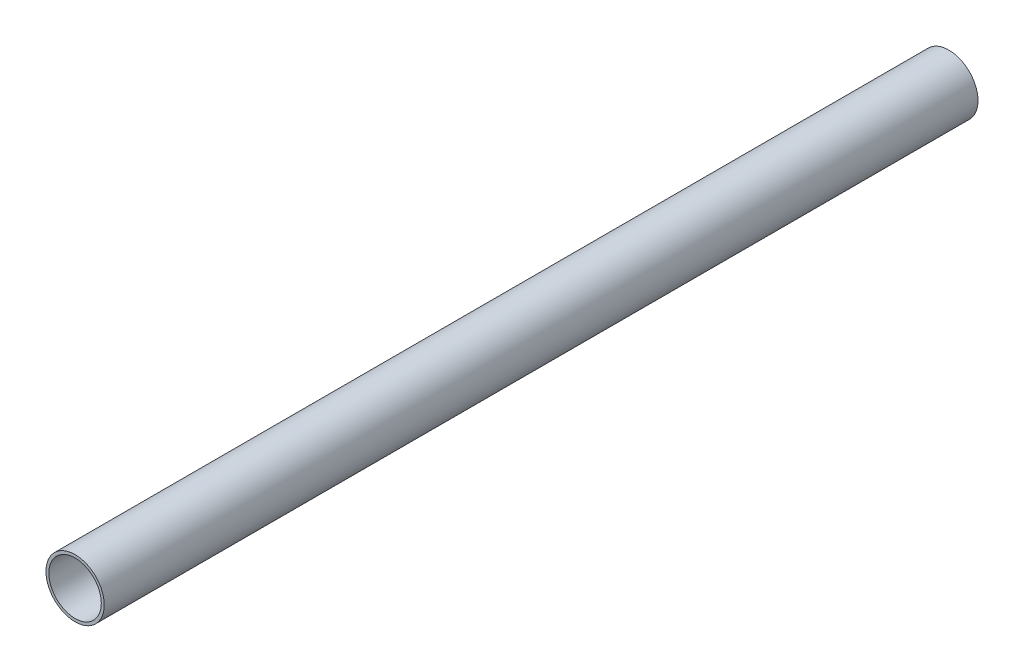
SolidWorks part; units mm, degrees
material "Thornel VCB-20 Carbon Cloth"
ref_plane "Front Plane" through (0, 0, 0) normal (0, 0, 1) x (1, 0, 0)
ref_plane "Top Plane" through (0, 0, 0) normal (0, 1, 0) x (1, 0, 0)
ref_plane "Right Plane" through (0, 0, 0) normal (1, 0, 0) x (0, 0, -1)
sketch "Sketch1" plane through (0, 0, 0) normal (0, 0, 1) x (1, 0, 0)
  circle A0 centre (0, 0) radius 9
  circle A1 centre (0, 0) radius 10
  dimension "D1" = 18
  dimension "D2" = 20
extrude "Boss-Extrude1" add sketch "Sketch1" along normal blind 300
equation "\"L\"= 300"
equation "\"D1@Boss-Extrude1\"=\"L\""
